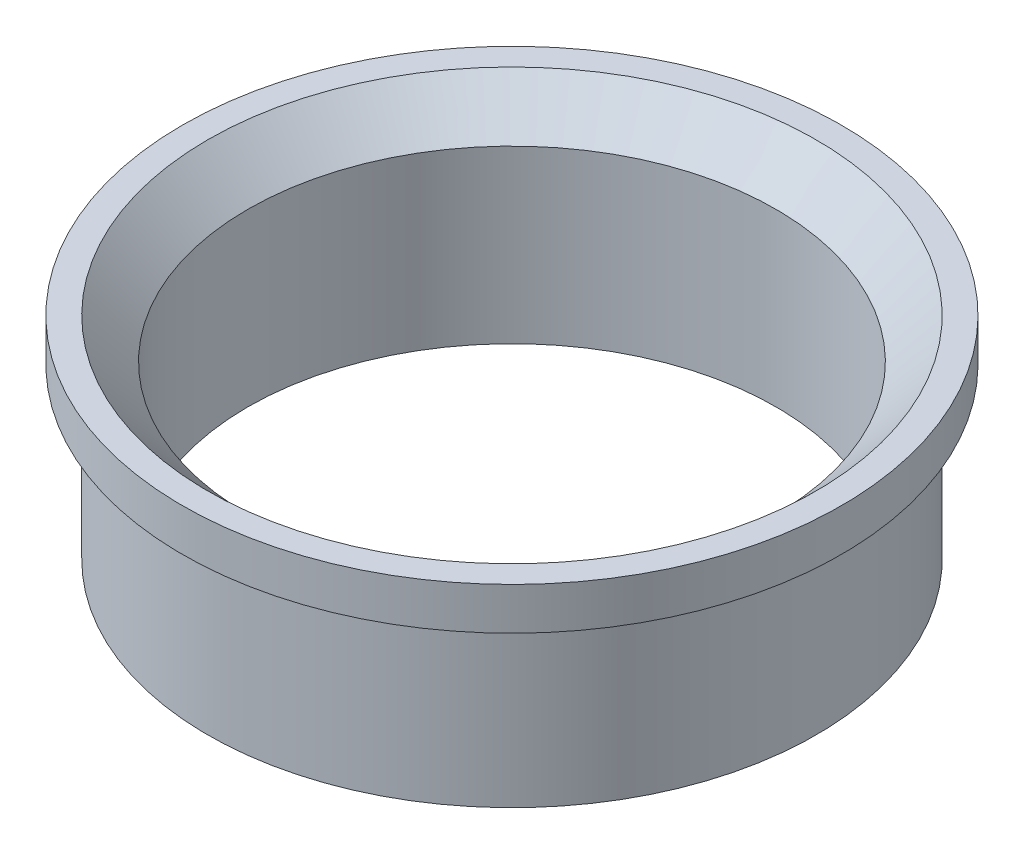
SolidWorks part; units mm, degrees
ref_plane "Front Plane" through (0, 0, 0) normal (0, 0, 1) x (1, 0, 0)
ref_plane "Top Plane" through (0, 0, 0) normal (0, 1, 0) x (1, 0, 0)
ref_plane "Right Plane" through (0, 0, 0) normal (1, 0, 0) x (0, 0, -1)
sketch "Sketch1" plane through (0, 0, 0) normal (0, 0, 1) x (1, 0, 0)
  line L0 (0, 0) -> (0, -98658.1021) construction
  line L1 (0, 0) -> (98658.1021, 0) construction
  line L2 (72, 0) -> (72, 40)
  line L3 (72, 40) -> (78, 40)
  line L4 (78, 40) -> (78, 50)
  line L5 (78, 50) -> (72, 50)
  line L6 (72, 50) -> (62.5, 40.5)
  line L7 (62.5, 40.5) -> (62.5, 0)
  line L8 (62.5, 0) -> (72, 0)
  point P7 (62.5, 40)
  dimension "D1" = 125
  dimension "D2" = 144
  dimension "D3" = 144
  dimension "D4" = 156
  dimension "D5" = 10
  dimension "D6" = 40
  dimension "D7" = 45
revolve "Revolve1" add sketch "Sketch1" angle 360 about L0
